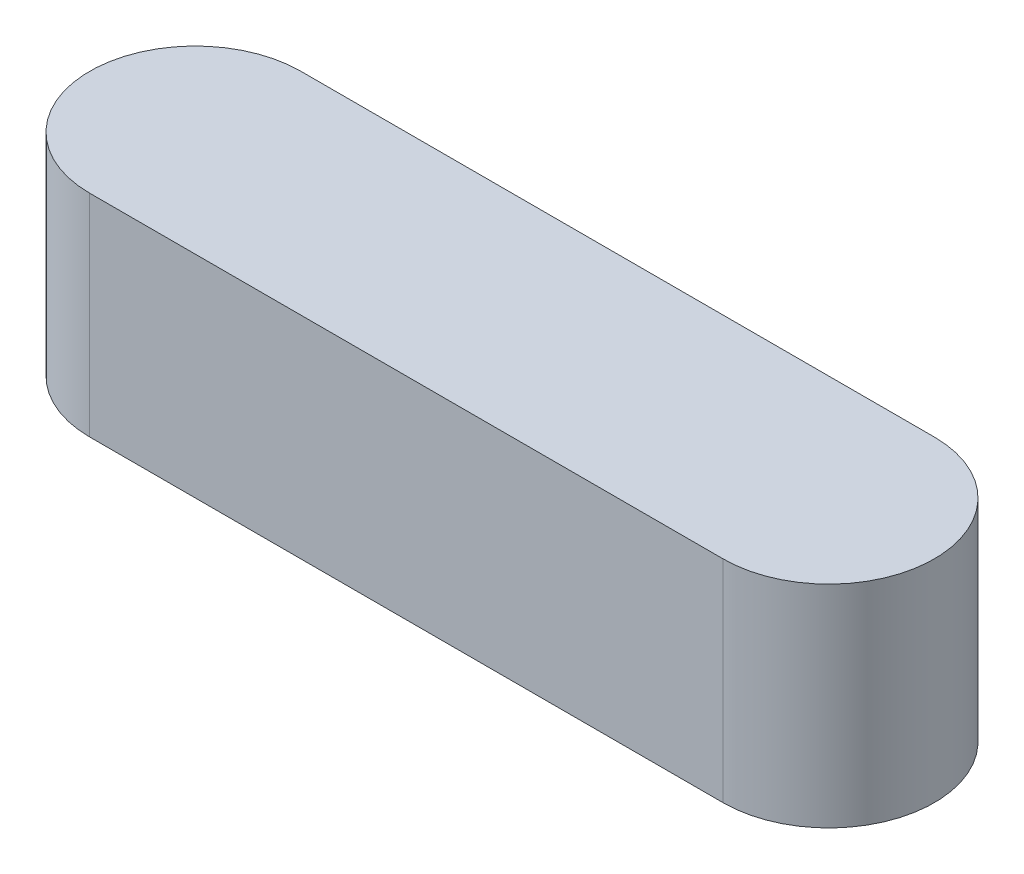
SolidWorks part; units mm, degrees
material "AISI 1020"
ref_plane "前视基准面" through (0, 0, 0) normal (0, 0, 1) x (1, 0, 0)
ref_plane "上视基准面" through (0, 0, 0) normal (0, 1, 0) x (1, 0, 0)
ref_plane "右视基准面" through (0, 0, 0) normal (1, 0, 0) x (0, 0, -1)
sketch "草图1" plane through (0, 0, 0) normal (0, 1, 0) x (1, 0, 0)
  line L0 (0, 0) -> (9, 0) construction
  line L1 (0, 1.5) -> (9, 1.5)
  line L2 (0, -1.5) -> (9, -1.5)
  arc A0 (0, 1.5) -> (0, -1.5) centre (0, 0) ccw
  arc A1 (9, -1.5) -> (9, 1.5) centre (9, 0) ccw
  point P3 (4.5, 0)
  dimension "D1" = 1.5
  dimension "D2" = 9
extrude "凸台-拉伸1" add sketch "草图1" along normal blind 3
